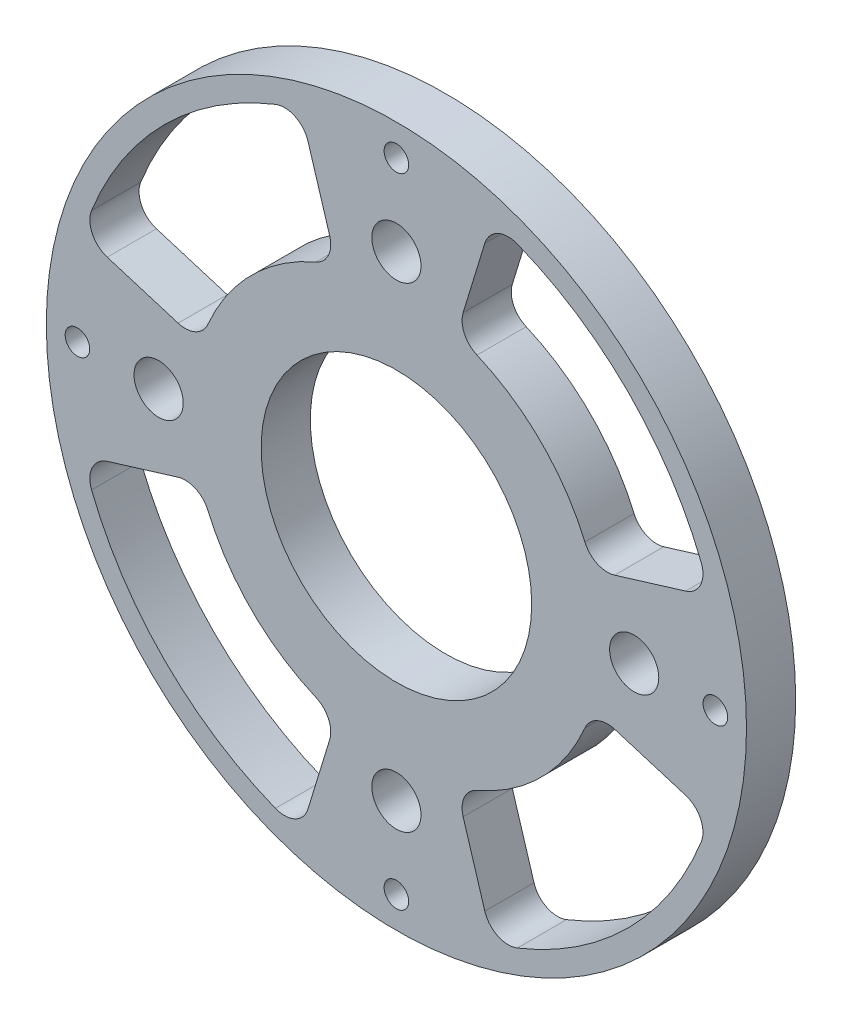
SolidWorks part; units mm, degrees
ref_plane "前视基准面" through (0, 0, 0) normal (0, 0, 1) x (1, 0, 0)
ref_plane "上视基准面" through (0, 0, 0) normal (0, 1, 0) x (1, 0, 0)
ref_plane "右视基准面" through (0, 0, 0) normal (1, 0, 0) x (0, 0, -1)
sketch "草图1" plane through (0, 0, 0) normal (0, 0, 1) x (1, 0, 0)
  line L0 (0, 0) -> (0, 29)
  line L1 (0, 0) -> (29, 0)
  line L2 (0, 0) -> (0, -29)
  line L3 (0, 0) -> (-29, 0)
  line L4 (0, 35) -> (0, 42.8)
  line L5 (-35, 0) -> (-42.8, 0)
  line L6 (0, -35) -> (0, -42.8)
  line L7 (35, 0) -> (42.8, 0)
  circle A0 centre (0, 0) radius 42.8
  circle A1 centre (0, 0) radius 18
  circle A2 centre (0, 0) radius 35
  circle A3 centre (0, 29) radius 3
  circle A4 centre (29, 0) radius 3
  circle A5 centre (0, -29) radius 3
  circle A6 centre (-29, 0) radius 3
sketch "草图2" plane through (0, 0, 0) normal (0, 0, 1) x (1, 0, 0)
  circle A0 centre (0, 0) radius 43
  circle A1 centre (0, 0) radius 16.5
extrude "凸台-拉伸1" add sketch "草图2" against normal blind 6
sketch "草图3" plane through (0, 0, 0) normal (0, 0, 1) x (1, 0, 0)
  line L0 (-35, 0) -> (-42.8, 0) construction
  line L1 (0, 35) -> (0, 42.8) construction
  line L2 (35, 0) -> (42.8, 0) construction
  line L3 (0, -35) -> (0, -42.8) construction
  circle A0 centre (0, 29) radius 3
  circle A1 centre (29, 0) radius 3
  circle A2 centre (0, -29) radius 3
  circle A3 centre (-29, 0) radius 3
  circle A4 centre (-38.9, 0) radius 1.5
  circle A5 centre (0, 38.9) radius 1.5
  circle A6 centre (38.9, 0) radius 1.5
  circle A7 centre (0, -38.9) radius 1.5
extrude "切除-拉伸1" cut sketch "草图3" against normal blind 6
sketch "草图4" plane through (0, 0, 0) normal (0, 0, 1) x (1, 0, 0)
  line L0 (0, 0) -> (-11.6949, 38.2522)
  line L1 (0, 0) -> (0, 29) construction
  line L2 (0, 0) -> (-38.2522, 11.6949)
  line L3 (0, 0) -> (-29, 0) construction
  line L4 (0, 0) -> (11.6949, 38.2522)
  line L5 (0, 0) -> (38.2522, 11.6949)
  line L6 (0, 0) -> (29, 0) construction
  line L7 (0, 0) -> (-38.2522, -11.6949)
  line L8 (0, 0) -> (38.2522, -11.6949)
  line L9 (0, 0) -> (11.6949, -38.2522)
  line L10 (0, 0) -> (0, -29) construction
  line L11 (0, 0) -> (-11.6949, -38.2522)
  circle A1 centre (0, 0) radius 25
  circle A3 centre (0, 0) radius 40
  dimension "D1" = 17
  dimension "D2" = 17
  dimension "D3" = 17
  dimension "D4" = 17
  dimension "D5" = 17
  dimension "D6" = 17
  dimension "D7" = 17
  dimension "D8" = 17
extrude "切除-拉伸5" cut sketch "草图4" against normal blind 6 contours L0 A3 L2 A1 | L5 A3 L4 A1 | L9 A3 L8 A1 | L7 A3 L11 A1
fillet "圆角2" radius 3 16 edges at (-23.9076, 7.3093, -3) (23.9076, 7.3093, -3) (11.6949, -38.2522, -3) (-11.6949, -38.2522, -3) (-38.2522, -11.6949, -3) (11.6949, 38.2522, -3) (23.9076, -7.3093, -3) (7.3093, -23.9076, -3) (-23.9076, -7.3093, -3) (-7.3093, -23.9076, -3) (-11.6949, 38.2522, -3) (-38.2522, 11.6949, -3) (7.3093, 23.9076, -3) (38.2522, -11.6949, -3) (38.2522, 11.6949, -3) (-7.3093, 23.9076, -3)
sketch "草图6" plane through (0, 0, 0) normal (0, 0, 1) x (1, 0, 0)
  circle A0 centre (0, 0) radius 43
  circle A1 centre (0, 0) radius 42.9
extrude "切除-拉伸6" cut sketch "草图6" against normal blind 6
sketch "草图7" plane through (0, 0, -6) normal (0, 0, -1) x (-1, 0, 0)
  circle A0 centre (0, 0) radius 42.7
  circle A1 centre (0, 0) radius 42.9
extrude "切除-拉伸7" cut sketch "草图7" against normal blind 6
